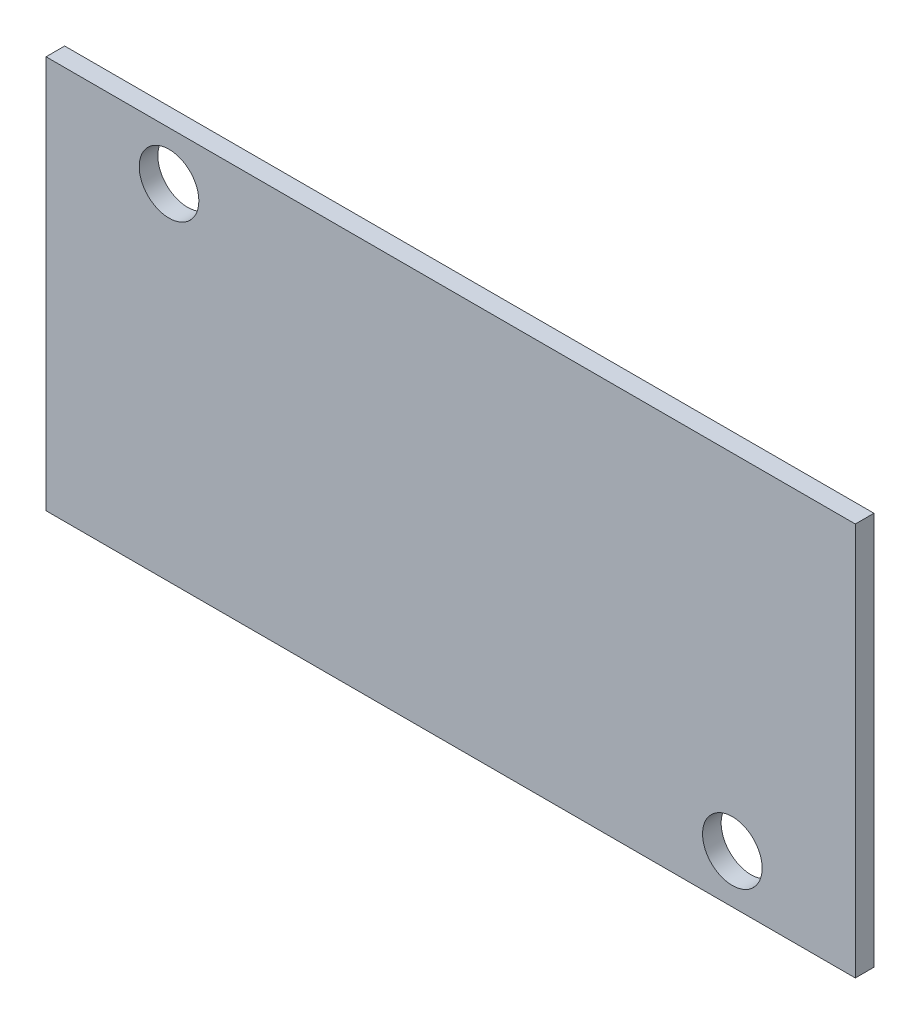
SolidWorks part; units mm, degrees
ref_plane "Alzado" through (0, 0, 0) normal (0, 0, 1) x (1, 0, 0)
ref_plane "Planta" through (0, 0, 0) normal (0, 1, 0) x (1, 0, 0)
ref_plane "Vista lateral" through (0, 0, 0) normal (1, 0, 0) x (0, 0, -1)
sketch "Croquis1" plane through (0, 0, 0) normal (0, 0, 1) x (1, 0, 0)
  line L0 (-13.515, 7.95) -> (-13.515, -16.67) construction
  line L1 (-21.715, 10.55) -> (21.715, 10.55)
  line L2 (-21.715, 10.55) -> (-21.715, -10.55)
  line L3 (-21.715, -10.55) -> (21.715, -10.55)
  line L4 (21.715, 10.55) -> (21.715, -10.55)
  line L5 (-21.715, 10.55) -> (21.715, -10.55) construction
  line L6 (-21.715, -10.55) -> (21.715, 10.55) construction
  line L7 (13.515, -7.95) -> (13.515, 14.404) construction
  line L8 (-15.115, 9.55) -> (-25.2678, 9.55) construction
  line L9 (-16.715, 7.95) -> (-16.715, 2.049) construction
  line L10 (15.115, -9.55) -> (24.8296, -9.55) construction
  line L11 (16.715, -7.95) -> (16.715, -1.4223) construction
  circle A0 centre (-15.115, 7.95) radius 1.6
  circle A1 centre (15.115, -7.95) radius 1.6
  point P0 (0, 0)
  dimension "D3" = 3.2
  dimension "D6" = 3.2
  dimension "D1" = 43.43
  dimension "D2" = 21.1
  dimension "D4" = 5
  dimension "D5" = 1
  dimension "D7" = 5
  dimension "D8" = 1
extrude "Saliente-Extruir1" add sketch "Croquis1" along normal blind 1
sketch "Croquis3" plane through (0, 0, 1) normal (0, 0, 1) x (1, 0, 0)
  line L0 (-13.5424, 8.2449) -> (-13.5424, -14.274) construction
  line L1 (13.5424, -8.2449) -> (13.5424, 15.3726) construction
  circle A0 centre (-15.115, 7.95) radius 1.6 construction
  circle A1 centre (15.115, -7.95) radius 1.6 construction
sketch "Croquis4" plane through (0, 0, 1) normal (0, 0, 1) x (1, 0, 0)
  line L0 (-15.115, 6.35) -> (28.4761, 6.35) construction
  line L1 (15.115, -6.35) -> (-19.8586, -6.35) construction
  circle A0 centre (-15.115, 7.95) radius 1.6 construction
  circle A1 centre (15.115, -7.95) radius 1.6 construction
